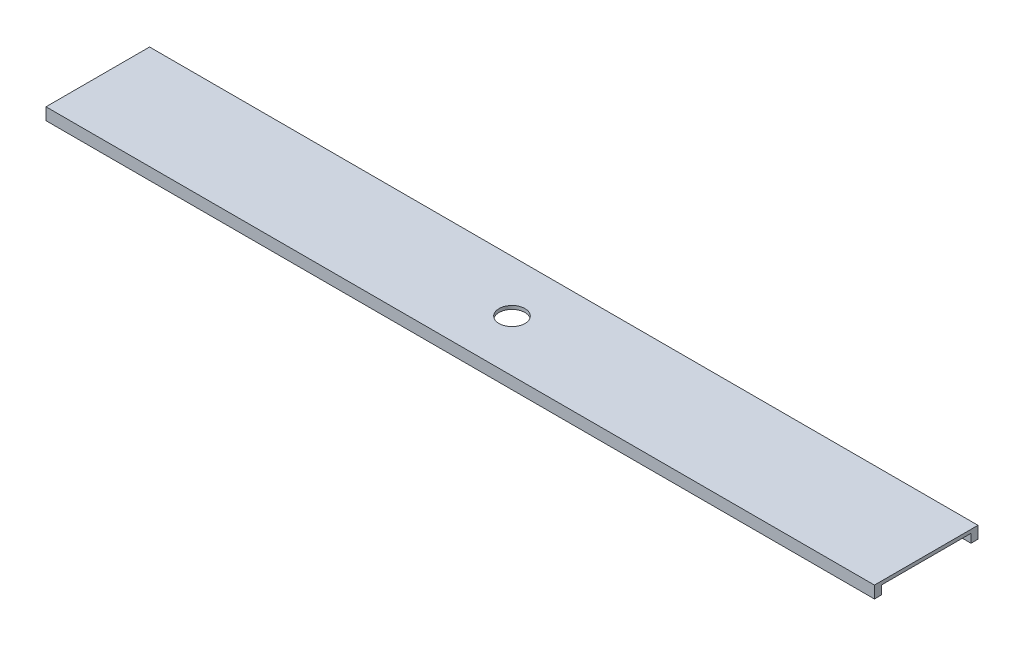
SolidWorks part; units mm, degrees
ref_plane "Front Plane" through (0, 0, 0) normal (0, 0, 1) x (1, 0, 0)
ref_plane "Top Plane" through (0, 0, 0) normal (0, 1, 0) x (1, 0, 0)
ref_plane "Right Plane" through (0, 0, 0) normal (1, 0, 0) x (0, 0, -1)
sketch "Sketch1" plane through (0, 0, 0) normal (0, 1, 0) x (1, 0, 0)
  line L1 (-480, 60) -> (480, 60)
  line L2 (-480, 60) -> (-480, -60)
  line L3 (-480, -60) -> (480, -60)
  line L4 (480, 60) -> (480, -60)
  line L5 (-480, 60) -> (480, -60) construction
  line L6 (-480, -60) -> (480, 60) construction
  point P0 (0, 0)
extrude "Boss-Extrude1" add sketch "Sketch1" along normal blind 4
sketch "Sketch2" plane through (0, 4, 0) normal (0, 1, 0) x (1, 0, 0)
  circle A0 centre (0, 0) radius 15
extrude "Cut-Extrude1" cut sketch "Sketch2" against normal blind 13 and the other way blind 24
sketch "Sketch3" plane through (0, 0, 0) normal (0, -1, 0) x (1, 0, 0)
  line L0 (480, 60) -> (480, -60) construction
  line L1 (-480, 60) -> (480, 60)
  line L2 (-480, 60) -> (-480, 51.651)
  line L3 (-480, 51.651) -> (480, 51.651)
  line L4 (480, 60) -> (480, 51.651)
extrude "Boss-Extrude2" add sketch "Sketch3" along normal blind 10
sketch "Sketch4" plane through (0, 0, 0) normal (0, -1, 0) x (1, 0, 0)
  line L0 (480, 51.651) -> (480, -60) construction
  line L1 (-480, -60) -> (480, -60)
  line L2 (-480, -60) -> (-480, -51.8863)
  line L3 (-480, -51.8863) -> (480, -51.8863)
  line L4 (480, -60) -> (480, -51.8863)
extrude "Boss-Extrude3" add sketch "Sketch4" along normal blind 10
